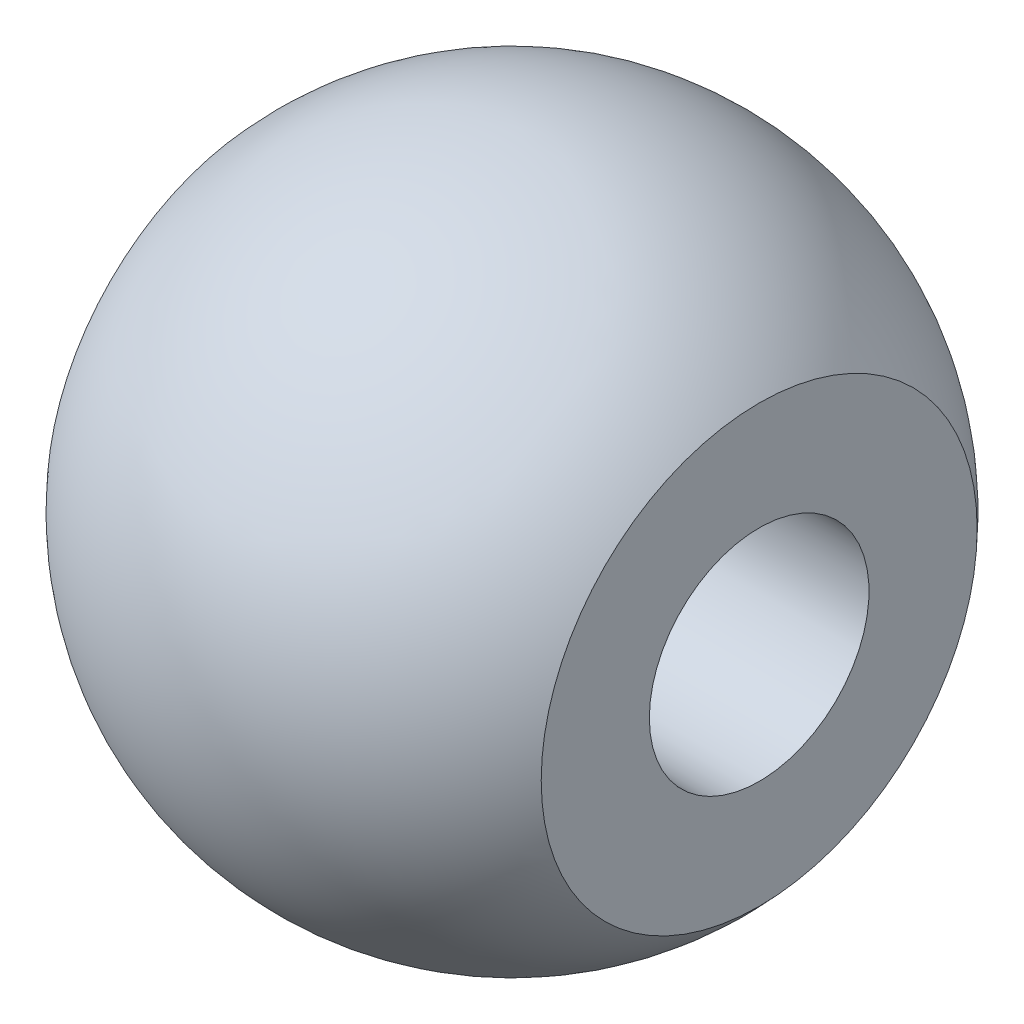
SolidWorks part; units mm, degrees
ref_plane "Front Plane" through (0, 0, 0) normal (0, 0, 1) x (1, 0, 0)
ref_plane "Top Plane" through (0, 0, 0) normal (0, 1, 0) x (1, 0, 0)
ref_plane "Right Plane" through (0, 0, 0) normal (1, 0, 0) x (0, 0, -1)
sketch "Sketch1" plane through (0, 0, 0) normal (0, 1, 0) x (1, 0, 0)
  line L0 (0, 6) -> (0, 0) construction
  line L1 (-4.5, 3.9686) -> (-4.5, 0)
  line L2 (4.5, 3.9686) -> (4.5, 0)
  line L3 (-4.5, 0) -> (4.5, 0)
  line L5 (4.5, 6) -> (4.5, -6) construction
  line L6 (0, 6) -> (0, -6) construction
  line L8 (-4.5, 6) -> (-4.5, -6) construction
  arc A0 (4.5, 3.9686) -> (-4.5, 3.9686) centre (0, 0) ccw
  dimension "D1" = 12
  dimension "D2" = 4.5
  dimension "D3" = 4.5
revolve "Revolve1" add sketch "Sketch1" angle 360 about L3
sketch "Sketch2" plane through (-4.5, 0, 0) normal (-1, 0, 0) x (0, 0, 1)
  circle A0 centre (0, 0) radius 2
  dimension "D1" = 4
extrude "Cut-Extrude1" cut sketch "Sketch2" against normal through all
chamfer "Chamfer1" distance 1 angle 45 1 edges at (-4.5, 0, 2)
